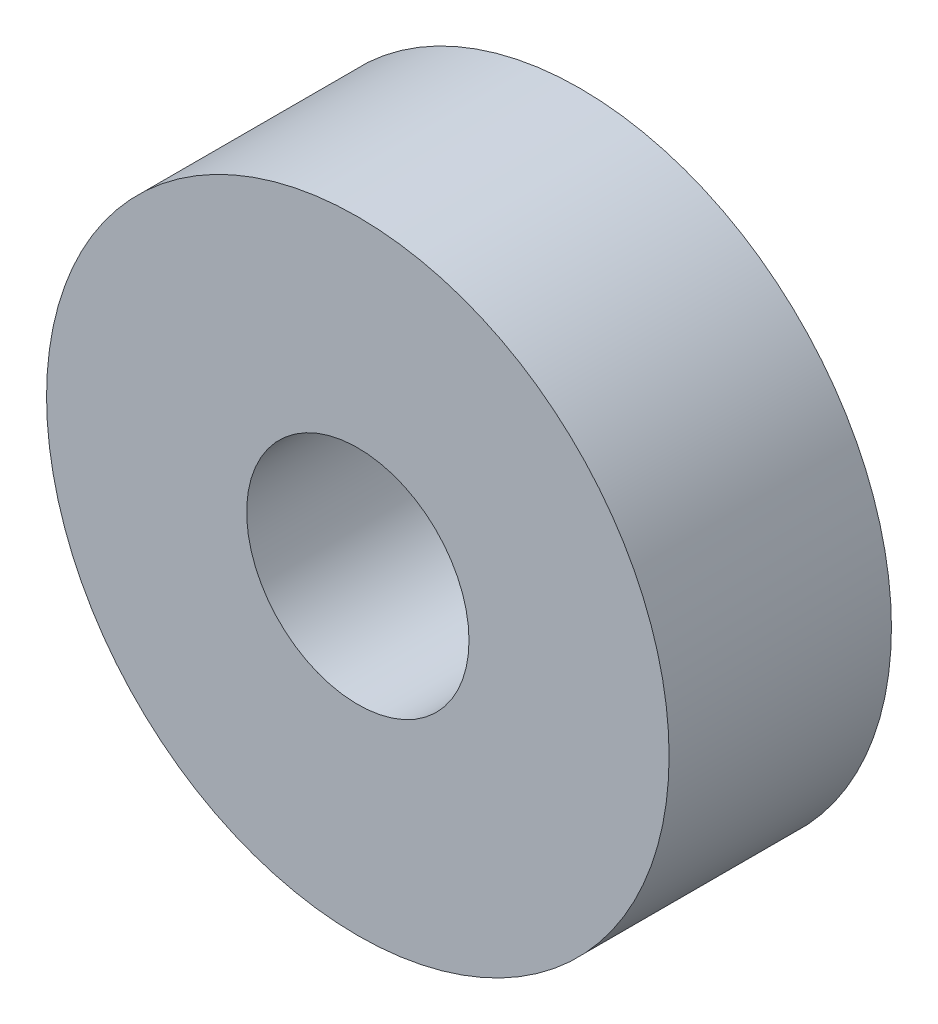
SolidWorks part; units mm, degrees
ref_plane "Plan de face" through (0, 0, 0) normal (0, 0, 1) x (1, 0, 0)
ref_plane "Plan de dessus" through (0, 0, 0) normal (0, 1, 0) x (1, 0, 0)
ref_plane "Plan de droite" through (0, 0, 0) normal (1, 0, 0) x (0, 0, -1)
sketch "Esquisse1" plane through (0, 0, 0) normal (0, 0, 1) x (1, 0, 0)
  circle A0 centre (0, 0) radius 2.5
  circle A1 centre (0, 0) radius 7
  dimension "D1" = 14
  dimension "D2" = 5
extrude "Boss.-Extru.1" add sketch "Esquisse1" along normal blind 5
